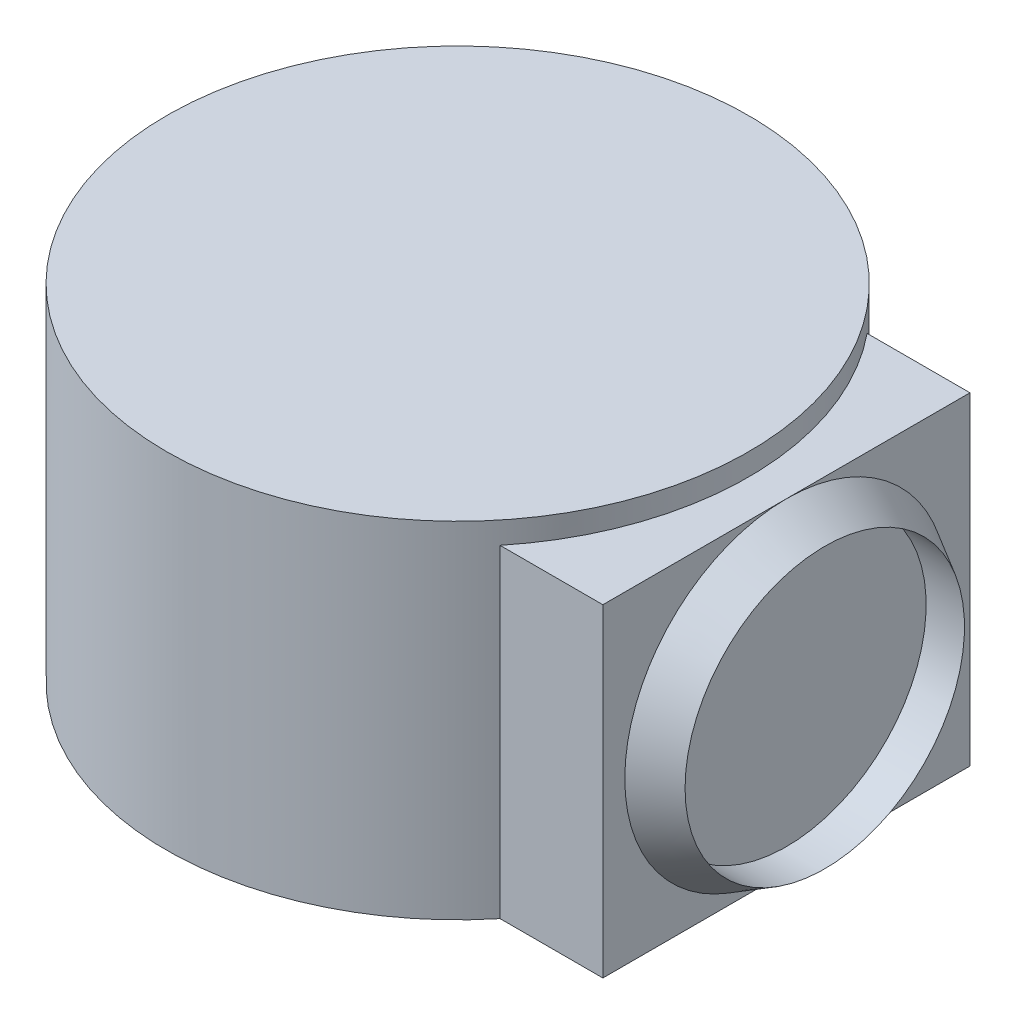
SolidWorks part; units mm, degrees
ref_plane "Front Plane" through (0, 0, 0) normal (0, 0, 1) x (1, 0, 0)
ref_plane "Top Plane" through (0, 0, 0) normal (0, 1, 0) x (1, 0, 0)
ref_plane "Right Plane" through (0, 0, 0) normal (1, 0, 0) x (0, 0, -1)
sketch "Sketch1" plane through (0, 0, 0) normal (0, 1, 0) x (1, 0, 0)
  circle A0 centre (0, 0) radius 132.8125
extrude "Boss-Extrude1" add sketch "Sketch1" along normal blind 147.5
sketch "Sketch2" plane through (0, 0, 0) normal (1, 0, 0) x (0, 0, -1)
  line L1 (132.8125, 147.5) -> (-132.8125, 147.5) construction
  line L3 (-83.75, 147.5) -> (-83.75, 0)
  line L4 (-132.8125, 0) -> (132.8125, 0) construction
  line L5 (-83.75, 0) -> (83.75, 0)
  line L6 (83.75, 0) -> (83.75, 147.5)
  line L7 (83.75, 147.5) -> (-83.75, 147.5)
extrude "Boss-Extrude2" add sketch "Sketch2" along normal blind 150
sketch "Sketch3" plane through (150, 0, 0) normal (1, 0, 0) x (0, 0, -1)
  line L0 (0, 0) -> (0, 20) construction
  line L1 (-83.75, 0) -> (83.75, 0) construction
sketch "Sketch4" plane through (0, 0, 0) normal (0, 0, 1) x (1, 0, 0)
  line L0 (150, 0) -> (150, 10)
  line L1 (150, 0) -> (150, 20) construction
  line L2 (150, 0) -> (150, 147.5) construction
  line L3 (150, 10) -> (167.5, 10)
  line L4 (167.5, 10) -> (150, 0)
  line L5 (150, 0) -> (150, 73.75) construction
  line L6 (150, 73.75) -> (215.633, 73.75) construction
revolve "Revolve1" add sketch "Sketch4" angle 360 about L6
sketch "Sketch5" plane through (0, 147.5, 0) normal (0, 1, 0) x (1, 0, 0)
  circle A0 centre (0, 0) radius 132.8125
extrude "Boss-Extrude3" add sketch "Sketch5" along normal blind 10
